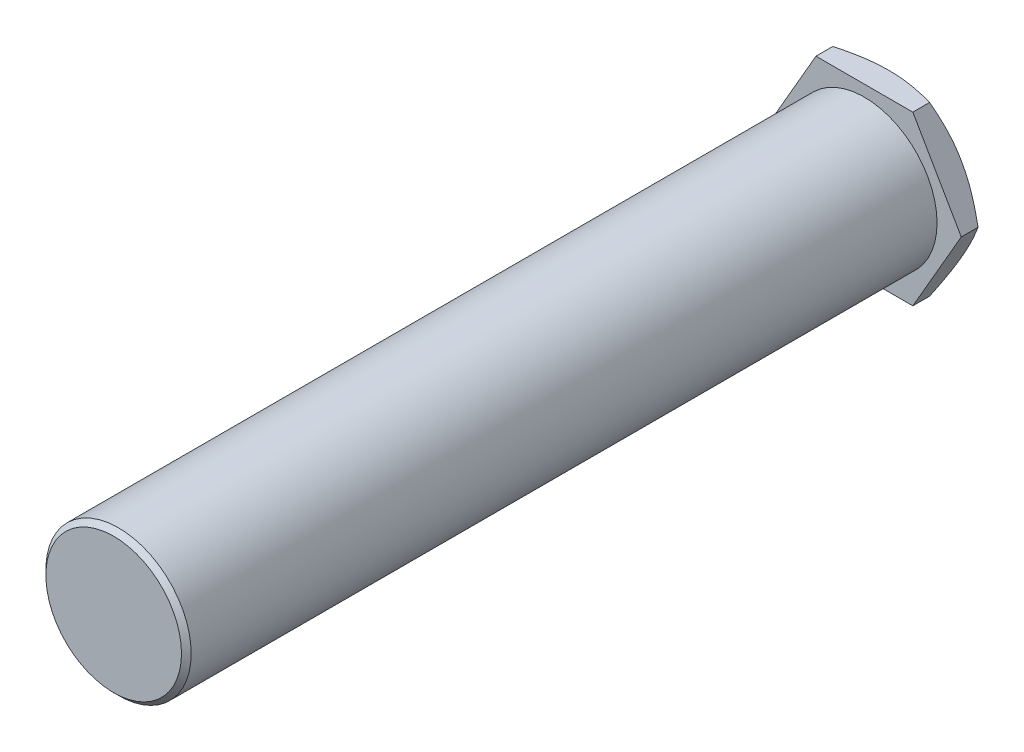
SolidWorks part; units mm, degrees
ref_plane "Płaszczyzna przednia" through (0, 0, 0) normal (0, 0, 1) x (1, 0, 0)
ref_plane "Płaszczyzna górna" through (0, 0, 0) normal (0, 1, 0) x (1, 0, 0)
ref_plane "Płaszczyzna prawa" through (0, 0, 0) normal (1, 0, 0) x (0, 0, -1)
sketch "Szkic1" plane through (0, 0, 0) normal (0, 0, 1) x (1, 0, 0)
  line L1 (10, 17.3205) -> (-10, 17.3205)
  line L2 (-10, 17.3205) -> (-20, 0)
  line L3 (-20, 0) -> (-10, -17.3205)
  line L4 (-10, -17.3205) -> (10, -17.3205)
  line L5 (10, -17.3205) -> (20, 0)
  line L6 (20, 0) -> (10, 17.3205)
  circle A0 centre (0, 0) radius 17.3205 construction
  dimension "D1" = 40
extrude "Dodanie-wyciągnięcie1" add sketch "Szkic1" along normal blind 5
sketch "Szkic2" plane through (0, 0, 0) normal (0, 0, 1) x (1, 0, 0)
  line L0 (-10, 17.3205) -> (-20, 0) construction
  circle A0 centre (0, 0) radius 17.3205
extrude "Wytnij-wyciągnięcie1" cut sketch "Szkic2" along normal blind 5 draft 60 flip side to cut
ref_plane "Płaszczyzna1" through (0, 0, 5) normal (0, 0, 1) x (1, 0, 0)
sketch "Szkic3" plane through (0, 0, 5) normal (0, 0, 1) x (1, 0, 0)
  circle A0 centre (0, 0) radius 15
  dimension "D1" = 30
extrude "Dodanie-wyciągnięcie2" add sketch "Szkic3" along normal blind 155
cosmetic thread "Oznaczenie gwintu3" parameters "D1"=30, "D2"=6.619
chamfer "Sfazowanie1" distance 1 angle 45 1 edges at (15, 0, 160)
equation "\"D1@Dodanie-wyciągnięcie2\" = 155"
equation "\"D1@Szkic3\"= 30"
equation "\"D1@Szkic1\" = 40"
